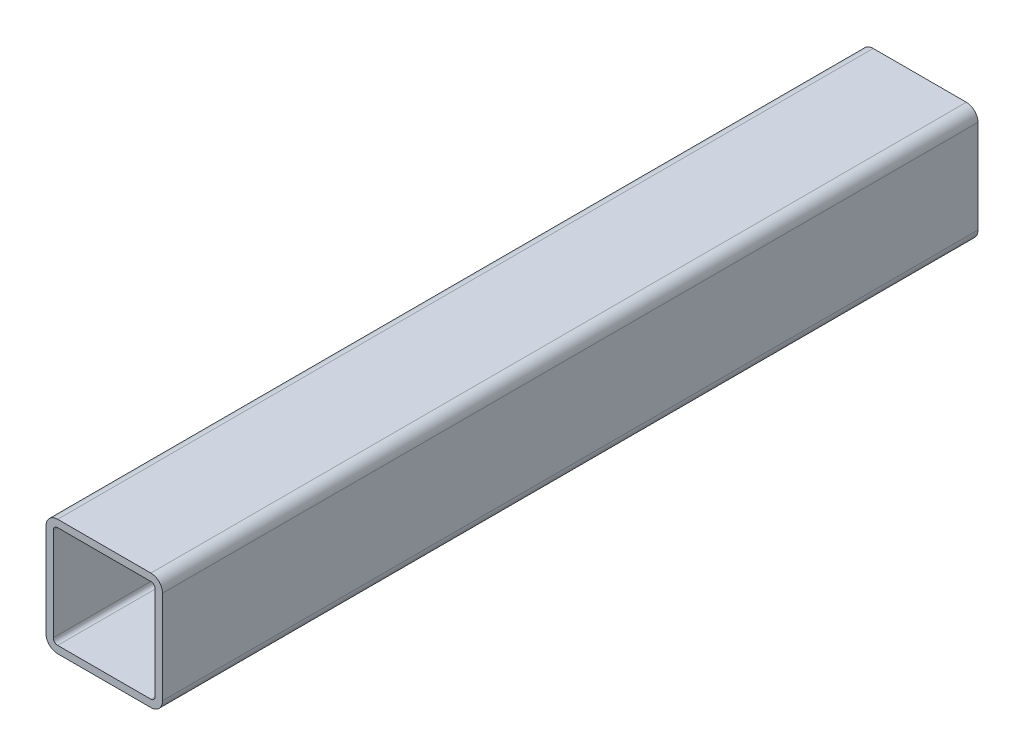
SolidWorks part; units mm, degrees
material "1.0037 (S235JR)"
ref_plane "Płaszczyzna przednia" through (0, 0, 0) normal (0, 0, 1) x (1, 0, 0)
ref_plane "Płaszczyzna górna" through (0, 0, 0) normal (0, 1, 0) x (1, 0, 0)
ref_plane "Płaszczyzna prawa" through (0, 0, 0) normal (1, 0, 0) x (0, 0, -1)
sketch "Szkic1" plane through (0, 0, 0) normal (0, 0, 1) x (1, 0, 0)
  line L1 (143, 0) -> (207, 0)
  line L2 (135, 8) -> (135, 72)
  line L3 (143, 80) -> (207, 80)
  line L4 (215, 8) -> (215, 72)
  line L6 (600, 8) -> (0, 8) construction
  line L7 (592, 80) -> (8, 80) construction
  line L8 (140, 8) -> (140, 72)
  line L9 (143, 75) -> (207, 75)
  line L10 (210, 8) -> (210, 72)
  line L11 (143, 5) -> (207, 5)
  arc A0 (215, 8) -> (207, 0) centre (207, 8) cw
  arc A1 (215, 72) -> (207, 80) centre (207, 72) ccw
  arc A2 (135, 8) -> (143, 0) centre (143, 8) ccw
  arc A3 (143, 80) -> (135, 72) centre (143, 72) ccw
  arc A4 (143, 75) -> (140, 72) centre (143, 72) ccw
  arc A5 (210, 72) -> (207, 75) centre (207, 72) ccw
  arc A6 (210, 8) -> (207, 5) centre (207, 8) cw
  arc A7 (140, 8) -> (143, 5) centre (143, 8) ccw
  dimension "D1" = 8
  dimension "D2" = 80
  dimension "D3" = 135
  dimension "D4" = 5
extrude "Dodanie-wyciągnięcie1" add sketch "Szkic1" along normal up to surface (560 mm away)
